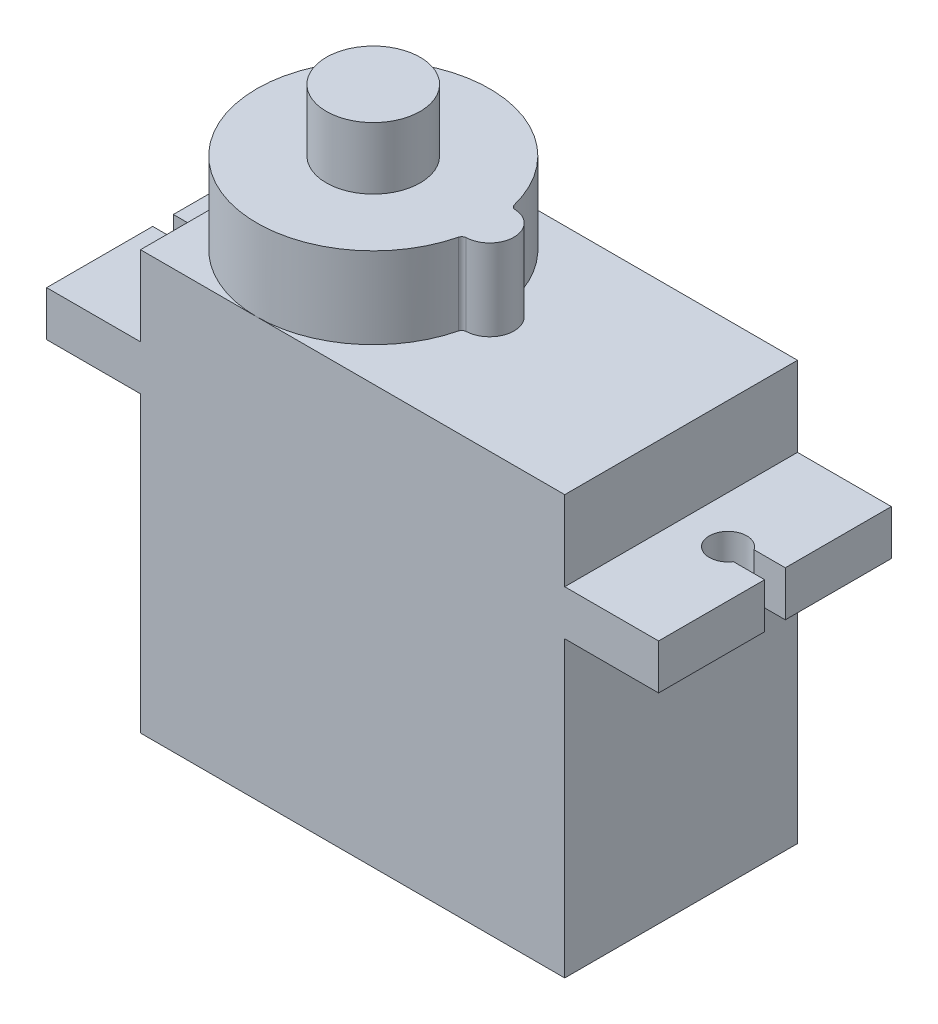
SolidWorks part; units mm, degrees
ref_plane "Front Plane" through (0, 0, 0) normal (0, 0, 1) x (1, 0, 0)
ref_plane "Top Plane" through (0, 0, 0) normal (0, 1, 0) x (1, 0, 0)
ref_plane "Right Plane" through (0, 0, 0) normal (1, 0, 0) x (0, 0, -1)
sketch "Sketch1" plane through (0, 0, 0) normal (0, 1, 0) x (1, 0, 0)
  line L1 (-11.3, 6.2) -> (11.3, 6.2)
  line L2 (-11.3, 6.2) -> (-11.3, -6.2)
  line L3 (-11.3, -6.2) -> (11.3, -6.2)
  line L4 (11.3, 6.2) -> (11.3, -6.2)
  line L5 (-11.3, 6.2) -> (11.3, -6.2) construction
  line L6 (-11.3, -6.2) -> (11.3, 6.2) construction
  point P0 (0, 0)
  dimension "D1" = 12.4
  dimension "D2" = 22.6
extrude "Boss-Extrude1" add sketch "Sketch1" along normal blind 22.3
sketch "Sketch2" plane through (0, 0, 6.2) normal (0, 0, 1) x (1, 0, 0)
  line L0 (11.3, 22.3) -> (11.3, 0) construction
  line L1 (11.3, 18.05) -> (16.3, 18.05)
  line L2 (11.3, 18.05) -> (11.3, 15.65)
  line L3 (11.3, 15.65) -> (16.3, 15.65)
  line L4 (16.3, 18.05) -> (16.3, 15.65)
  line L5 (-11.3, 22.3) -> (11.3, 22.3) construction
  line L6 (0, 0) -> (0, 7.7907) construction
  line L7 (-16.3, 18.05) -> (-16.3, 15.65)
  line L8 (-11.3, 15.65) -> (-16.3, 15.65)
  line L9 (-11.3, 18.05) -> (-11.3, 15.65)
  line L10 (-11.3, 18.05) -> (-16.3, 18.05)
  dimension "D1" = 2.4
  dimension "D2" = 5
  dimension "D3" = 4.25
extrude "Boss-Extrude2" add sketch "Sketch2" against normal up to vertex (12.4 mm away)
sketch "Sketch3" plane through (0, 18.05, 0) normal (0, 1, 0) x (1, 0, 0)
  line L0 (14.6352, 0.55) -> (16.3, 0.55)
  line L1 (16.3, 6.2) -> (16.3, -6.2) construction
  line L2 (16.3, 0.55) -> (16.3, -0.55)
  line L3 (16.3, -0.55) -> (14.6352, -0.55)
  line L4 (0, 0) -> (13.8, 0) construction
  circle A0 centre (13.8, 0) radius 1
  dimension "D1" = 2
  dimension "D3" = 2.5
  dimension "D2" = 1.1
extrude "s" cut sketch "Sketch3" against normal through all
mirror "Mirror1" about plane through (0, 0, 0) normal (1, 0, 0) of "s"
sketch "Sketch4" plane through (0, 22.3, 0) normal (0, 1, 0) x (1, 0, 0)
  line L0 (-11.3, 6.2) -> (-11.3, -6.2) construction
  line L1 (11.3, 6.2) -> (-11.3, 6.2) construction
  arc A0 (0.9186, 1.4888) -> (0.9186, -1.4888) centre (-5.1, 0) ccw
  arc A1 (1.1514, -1.299) -> (1.1514, 1.299) centre (1.1, 0) ccw
  arc A2 (1.1514, -1.299) -> (0.9186, -1.4888) centre (1.1613, -1.5488) ccw
  arc A3 (1.1514, 1.299) -> (0.9186, 1.4888) centre (1.1613, 1.5488) cw
  dimension "D1" = 12.4
  dimension "D2" = 2.6
  dimension "D3" = 0.25
extrude "Boss-Extrude3" add sketch "Sketch4" along normal blind 4.33
sketch "Sketch5" plane through (0, 26.63, 0) normal (0, 1, 0) x (1, 0, 0)
  circle A0 centre (-5.1, 0) radius 2.5
  dimension "D1" = 5
extrude "Boss-Extrude4" add sketch "Sketch5" along normal blind 3.3
sketch "Sketch6" plane through (-11.3, 0, 0) normal (-1, 0, 0) x (0, 0, 1)
  line L0 (-6.2, 0) -> (6.2, 0) construction
  circle A0 centre (0, 4.5) radius 0.6
  circle A1 centre (1.2, 4.5) radius 0.6
  circle A2 centre (-1.2, 4.5) radius 0.6
  dimension "D1" = 1.2
  dimension "D2" = 4.5
extrude "Boss-Extrude6" add sketch "Sketch6" along normal blind 2.3 separate body contours A1 | A0 | A2
